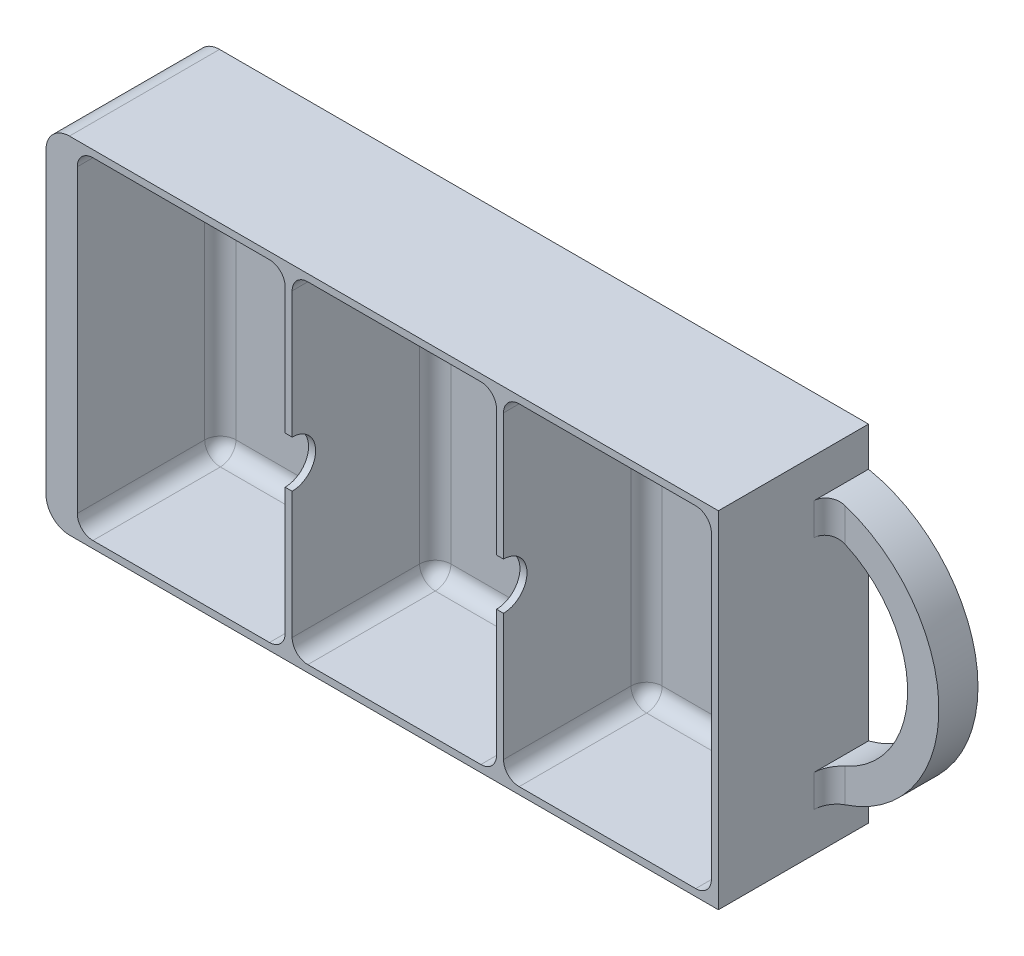
SolidWorks part; units mm, degrees
ref_plane "Спереди" through (0, 0, 0) normal (0, 0, 1) x (1, 0, 0)
ref_plane "Сверху" through (0, 0, 0) normal (0, 1, 0) x (1, 0, 0)
ref_plane "Справа" through (0, 0, 0) normal (1, 0, 0) x (0, 0, -1)
ref_plane "Плоскость4" through (0, 0, 9.6) normal (0, 0, 1) x (1, 0, 0)
sketch "Эскиз1" plane through (0, 0, 9.6) normal (0, 0, 1) x (1, 0, 0)
  line L0 (90, -22.1) -> (90, 22.1)
  line L1 (90, 22.1) -> (4, 22.1)
  line L2 (4, 22.1) -> (4, -22.1)
  line L3 (4, -22.1) -> (90, -22.1)
extrude "Бобышка-Вытянуть1" add sketch "Эскиз1" against normal blind 14.2
sketch "Эскиз2" plane through (0, 0, -4.6) normal (0, 0, -1) x (-1, 0, 0)
  line L0 (-90, -22.1) -> (-90, -17.1)
  line L1 (-90, 17.1) -> (-90, 22.1)
  line L2 (-90, 22.1) -> (-4, 22.1)
  line L3 (-4, 22.1) -> (-4, -22.1)
  line L4 (-4, -22.1) -> (-90, -22.1)
  line L5 (-90, -12.9948) -> (-90, 12.9948)
  arc A0 (-90, -17.1) -> (-90, 17.1) centre (-86.5568, 0) cw
  arc A1 (-90, 12.9948) -> (-90, -12.9948) centre (-86.5568, 0) ccw
extrude "Бобышка-Вытянуть2" add sketch "Эскиз2" along normal blind 5
sketch "Эскиз3" plane through (0, 0, 9.6) normal (0, 0, 1) x (1, 0, 0)
  line L0 (62.516, 21.2) -> (62.516, -21.2)
  line L1 (62.516, -21.2) -> (89.1, -21.2)
  line L2 (89.1, -21.2) -> (89.1, 21.2)
  line L3 (89.1, 21.2) -> (62.516, 21.2)
extrude "Вырез-Вытянуть1" cut sketch "Эскиз3" against normal blind 18.3
sketch "Эскиз4" plane through (0, 0, 9.6) normal (0, 0, 1) x (1, 0, 0)
  line L0 (8, 21.2) -> (8, -21.2)
  line L1 (8, -21.2) -> (34.583, -21.2)
  line L2 (34.583, -21.2) -> (34.583, 21.2)
  line L3 (34.583, 21.2) -> (8, 21.2)
extrude "Вырез-Вытянуть2" cut sketch "Эскиз4" against normal blind 18.3
sketch "Эскиз5" plane through (0, 0, 9.6) normal (0, 0, 1) x (1, 0, 0)
  line L0 (61.616, -21.2) -> (61.616, 21.2)
  line L1 (61.616, 21.2) -> (35.483, 21.2)
  line L2 (35.483, 21.2) -> (35.483, -21.2)
  line L3 (35.483, -21.2) -> (61.616, -21.2)
extrude "Вырез-Вытянуть3" cut sketch "Эскиз5" against normal blind 18.3
hole_wizard "Диаметр отверстия Ø8.3 (8.3)1" positions "Эскиз7" profile "Эскиз6" hole size "Ø8.3" standard "Ansi Metric"
sketch "Эскиз7" plane through (4, 0, 0) normal (-1, 0, 0) x (0, 0, 1)
  point P0 (0, 0)
sketch "Эскиз6" plane through (4, 0, 0) normal (0, 1, 0) x (0, 0, 1)
  line L0 (0, 0) -> (0, 3.2)
  line L1 (0, 3.2) -> (4.15, 3.2)
  line L2 (4.15, 3.2) -> (4.15, 0)
  line L5 (4.15, 0) -> (0, 0)
  line L10 (0, 3.2) -> (-4.15, 3.2) construction
  line L11 (0, -6.35) -> (0, 107.95) construction
  dimension "Диаметр отверстия" = 8.3
  dimension "Глубина отверстия" = 3.2
  dimension "Угол заточки сверла" = 180
hole_wizard "Диаметр отверстия Ø6.0 (6)1" positions "Эскиз9" profile "Эскиз8" hole size "Ø6.0" standard "Ansi Metric"
sketch "Эскиз9" plane through (61.616, 0, 0) normal (-1, 0, 0) x (0, 0, 1)
  point P0 (9.6, 0)
sketch "Эскиз8" plane through (61.616, 0, 9.6) normal (0, 1, 0) x (0, 0, 1)
  line L0 (0, 0) -> (0, 0.9)
  line L1 (0, 0.9) -> (3, 0.9)
  line L2 (3, 0.9) -> (3, 0)
  line L5 (3, 0) -> (0, 0)
  line L11 (0, -6.35) -> (0, 107.95) construction
  dimension "Диаметр сквозного отверстия" = 6
  dimension "Глубина сквозного отверстия" = 0.9
hole_wizard "Диаметр отверстия Ø6.0 (6)2" positions "Эскиз11" profile "Эскиз10" hole size "Ø6.0" standard "Ansi Metric"
sketch "Эскиз11" plane through (35.483, 0, 0) normal (1, 0, 0) x (0, 0, -1)
  point P0 (-9.6, 0)
sketch "Эскиз10" plane through (35.483, 0, 9.6) normal (0, 1, 0) x (0, 0, -1)
  line L0 (0, 0) -> (0, 0.9)
  line L1 (0, 0.9) -> (3, 0.9)
  line L2 (3, 0.9) -> (3, 0)
  line L5 (3, 0) -> (0, 0)
  line L11 (0, -6.35) -> (0, 107.95) construction
  dimension "Диаметр сквозного отверстия" = 6
  dimension "Глубина сквозного отверстия" = 0.9
fillet "Скругление1" radius 3 2 edges at (4, -22.1, 0) (4, 22.1, 0)
sketch "Эскиз12" plane through (4, 0, 0) normal (-1, 0, 0) x (0, 0, 1)
  circle A0 centre (0, 0) radius 4.15 construction
  circle A1 centre (0, 0) radius 4.15
extrude "Бобышка-Вытянуть3" add sketch "Эскиз12" against normal blind 3.5
fillet "Скругление2" radius 2 26 edges at (34.583, 0, -8.7) (21.2915, -21.2, -8.7) (8, 0, -8.7) (21.2915, 21.2, -8.7) (89.1, 0, -8.7) (75.808, -21.2, -8.7) (62.516, 0, -8.7) (75.808, 21.2, -8.7) (90, -15.0474, -4.6) (90, 15.0474, -4.6) (62.516, -21.2, 0.45) (89.1, -21.2, 0.45) (89.1, 21.2, 0.45) (62.516, 21.2, 0.45) (61.616, -21.2, 0.45) (48.5495, -21.2, -8.7) (61.616, 0, -8.7) (61.616, 21.2, 0.45) (35.483, -21.2, 0.45) (34.583, -21.2, 0.45) (48.5495, 21.2, -8.7) (35.483, 0, -8.7) (35.483, 21.2, 0.45) (34.583, 21.2, 0.45) (8, 21.2, 0.45) (8, -21.2, 0.45)
